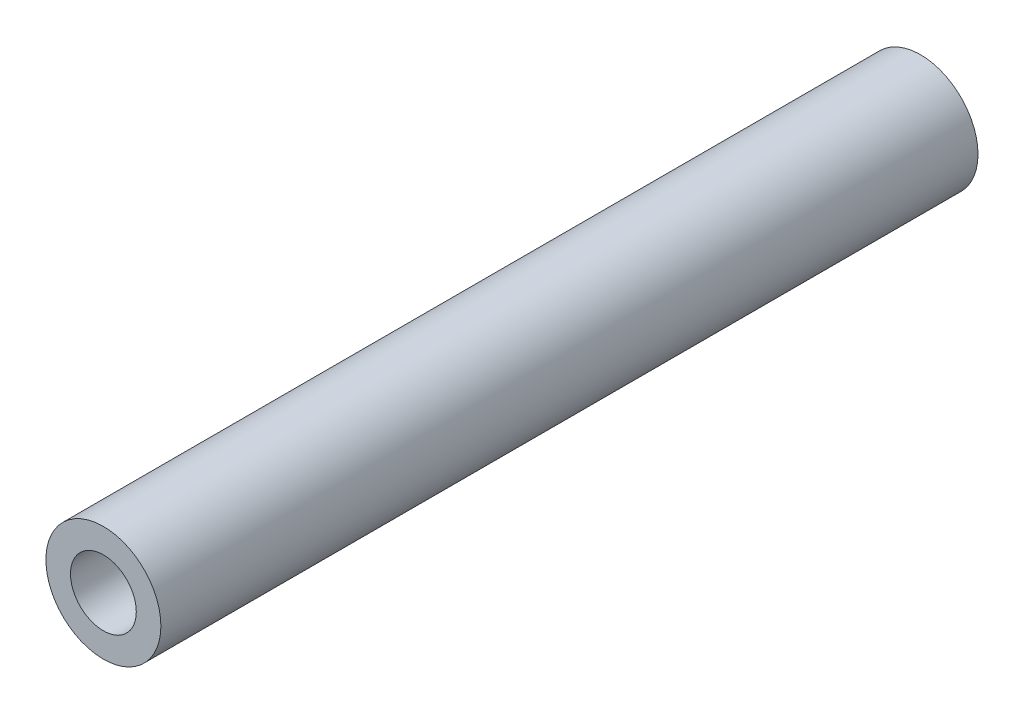
SolidWorks part; units mm, degrees
ref_plane "Front Plane" through (0, 0, 0) normal (0, 0, 1) x (1, 0, 0)
ref_plane "Top Plane" through (0, 0, 0) normal (0, 1, 0) x (1, 0, 0)
ref_plane "Right Plane" through (0, 0, 0) normal (1, 0, 0) x (0, 0, -1)
sketch "Sketch1" plane through (0, 0, 0) normal (0, 0, 1) x (1, 0, 0)
  circle A0 centre (1803.9912, -1743.8494) radius 4.63
  circle A1 centre (1803.9912, -1743.8494) radius 2.65
extrude "Boss-Extrude1" add sketch "Sketch1" along normal up to surface (65.8 mm away)
